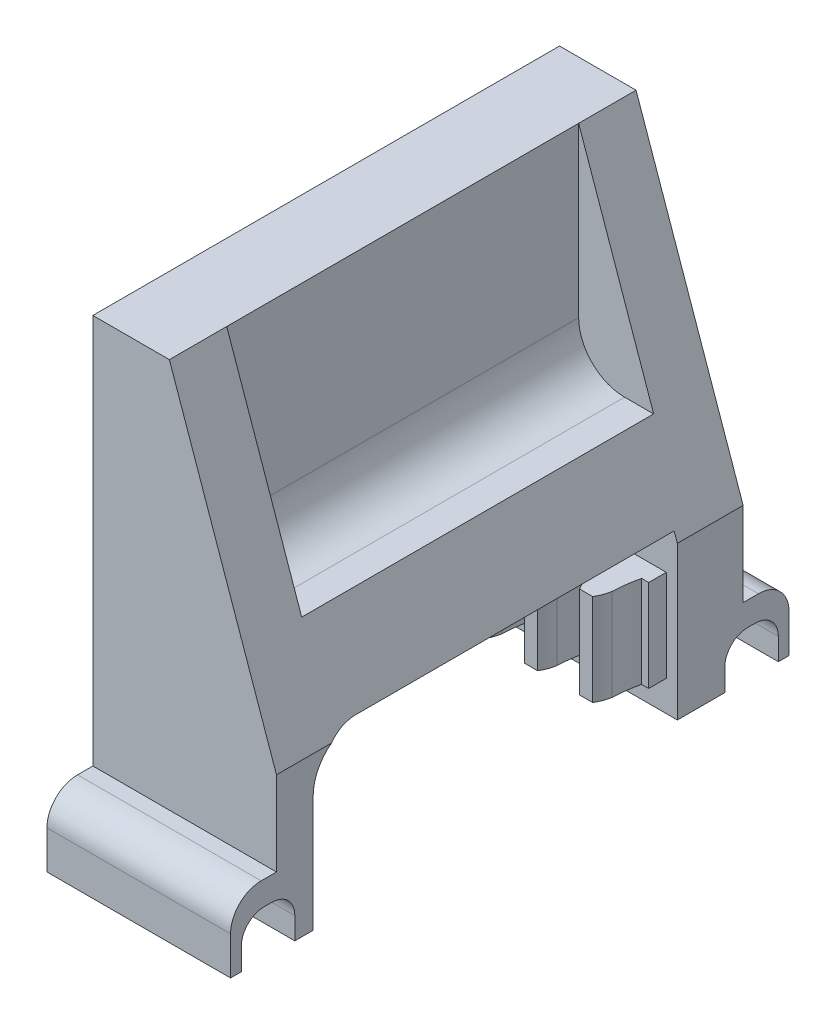
SolidWorks part; units mm, degrees
ref_plane "Front Plane" through (0, 0, 0) normal (0, 0, 1) x (1, 0, 0)
ref_plane "Top Plane" through (0, 0, 0) normal (0, 1, 0) x (1, 0, 0)
ref_plane "Right Plane" through (0, 0, 0) normal (1, 0, 0) x (0, 0, -1)
sketch "Sketch1" plane through (0, 0, 0) normal (0, 0, 1) x (1, 0, 0)
  line L0 (0, 0) -> (0, -30)
  line L1 (0, -30) -> (12, -30)
  line L2 (12, -30) -> (12, -20)
  line L3 (12, -20) -> (5, 0)
  line L4 (5, 0) -> (0, 0)
  dimension "D1" = 30
  dimension "D2" = 12
  dimension "D3" = 10
  dimension "D4" = 5
extrude "Boss-Extrude1" add sketch "Sketch1" against normal blind 30.5
sketch "Sketch4" plane through (0, 0, 0) normal (-1, 0, 0) x (0, 0, 1)
  line L0 (-30.5, 0) -> (-30.5, -30) construction
  line L1 (-26.2, -19.3999) -> (-2.4, -19.3999)
  line L2 (-26.2, -19.3999) -> (-26.2, -32.3999)
  line L3 (-26.2, -32.3999) -> (-2.4, -32.3999)
  line L4 (-2.4, -19.3999) -> (-2.4, -32.3999)
  point P4 (-26.2, -25.8999)
  dimension "D1" = 23.8
  dimension "D2" = 13
  dimension "D3" = 4.3
extrude "Cut-Extrude2" cut sketch "Sketch4" against normal blind 25 contours L2 L1 L4 L3
ref_plane "Plane1" through (0, 0, -15.25) normal (0, 0, 1) x (1, 0, 0)
sketch "Sketch6" plane through (0, 0, -15.25) normal (0, 0, 1) x (1, 0, 0)
  line L0 (5, 0) -> (5, -14)
  line L1 (5, -14) -> (9.9, -14)
  line L2 (12, -20) -> (5, 0) construction
  line L3 (9.9, -14) -> (5, 0)
  dimension "D1" = 14
extrude "Cut-Extrude4" cut sketch "Sketch6" against normal mid plane 23
ref_plane "Plane2" through (0, -26.4, 0) normal (0, 1, 0) x (1, 0, 0)
ref_plane "Plane3" through (0, -28, 0) normal (0, 1, 0) x (1, 0, 0)
sketch "Sketch7" plane through (0, -28, 0) normal (0, 1, 0) x (1, 0, 0)
  line L0 (11.2768, 26.75) -> (-19.7232, 26.75)
  line L62 (-6.6, 15.25) -> (6.6, 15.25) construction
  line L162 (11.2768, 26.75) -> (11.2768, 25.05)
  line L172 (-19.7232, 25.05) -> (-19.7232, 26.75)
  line L243 (11.2768, 25.05) -> (-19.7232, 25.05)
  dimension "D2" = 31
  dimension "D3" = 1.7
  dimension "D7" = 11.5
extrude "Boss-Extrude3" add sketch "Sketch7" along normal blind 6
sketch "Sketch10" plane through (0, -28, 0) normal (0, 1, 0) x (1, 0, 0)
  line L1 (9.8114, 22.4222) -> (9.8114, 23.4692) construction
  line L2 (10.2413, 22.4222) -> (9.3814, 22.4222)
  line L4 (-19.7232, 25.05) -> (11.2768, 25.05) construction
  line L5 (8.8114, 25.05) -> (10.8114, 25.05)
  arc A0 (10.2413, 22.4222) -> (10.5856, 23.3402) centre (8.0997, 23.7488) ccw
  arc A1 (10.5856, 23.3402) -> (10.8114, 25.05) centre (19.7752, 22.9964) cw
  arc A2 (9.0372, 23.3402) -> (8.8114, 25.05) centre (-0.1525, 22.9964) ccw
  arc A3 (9.3814, 22.4222) -> (9.0372, 23.3402) centre (11.523, 23.7488) cw
  point P7 (9.7183, 23.0818)
  point P15 (10.1348, 23.3259)
  dimension "D1" = 2
extrude "Boss-Extrude4" add sketch "Sketch10" along normal blind 6
pattern_linear "LPattern1" count 8 spacing 3.6 along (-1, 0, 0) of "Boss-Extrude4"
sketch "Sketch11" plane through (0, 0, -30.5) normal (0, 0, -1) x (-1, 0, 0)
  line L0 (-12, -30) -> (-12, -20) construction
  line L1 (-12, -25.5) -> (0, -25.5)
  line L2 (-12, -25.5) -> (-12, -30)
  line L3 (-12, -30) -> (0, -30)
  line L4 (0, -25.5) -> (0, -30)
  dimension "D1" = 4.5
extrude "Boss-Extrude5" add sketch "Sketch11" along normal blind 3
fillet "Fillet1" radius 2 1 edges at (6, -25.5, -33.5)
mirror "Mirror1" about plane through (0, 0, -15.25) normal (0, 0, 1) of "Boss-Extrude5"
fillet "Fillet2" radius 2 1 edges at (6, -25.5, 3)
fillet "Fillet5" radius 3 2 edges at (5, -14, -15.25) (5.895, -19.3999, -2.4)
sketch "Sketch12" plane through (0, 0, 0) normal (-1, 0, 0) x (0, 0, 1)
  line L0 (-15.25, -20.6354) -> (-15.25, -36.9741) construction
  line L1 (-32.8, -27.0644) -> (-29.3, -27.0644)
  line L2 (-32.8, -27.0644) -> (-32.8, -30.5644)
  line L3 (-32.8, -30.5644) -> (-29.3, -30.5644)
  line L4 (-29.3, -27.0644) -> (-29.3, -30.5644)
  line L5 (-2.4, -30) -> (-2.4, -22.3999) construction
  line L11 (-15.25, -6.6) -> (-15.25, 6.6) construction
  line L12 (2.3, -30.5644) -> (-1.2, -30.5644)
  line L13 (-1.2, -27.0644) -> (-1.2, -30.5644)
  line L14 (2.3, -27.0644) -> (-1.2, -27.0644)
  line L15 (2.3, -27.0644) -> (2.3, -30.5644)
  dimension "D1" = 3.5
  dimension "D2" = 3.5
  dimension "D3" = 1.2
extrude "Cut-Extrude5" cut sketch "Sketch12" against normal up to surface (12 mm away) up to face at (12, -25.043, -0.0878)
fillet "Fillet6" radius 1.5 4 edges at (6, -27.0644, -32.8) (6, -27.0644, -29.3) (6, -27.0644, 2.3) (6, -27.0644, -1.2)
